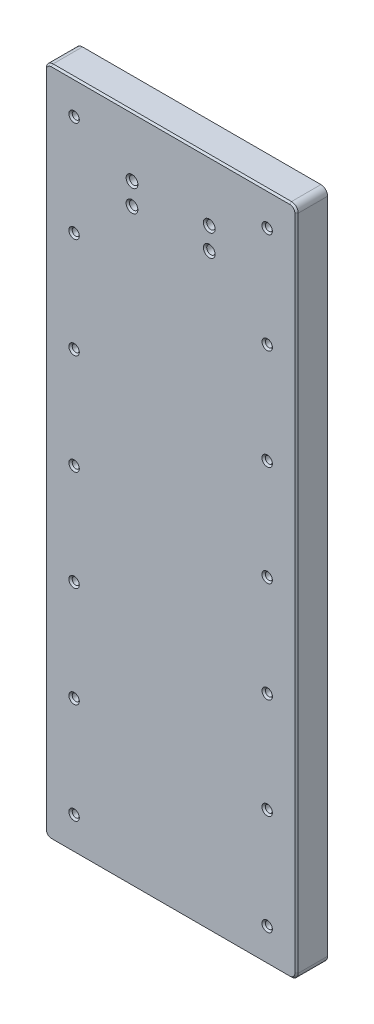
SolidWorks part; units mm, degrees
ref_plane "Front Plane" through (0, 0, 0) normal (0, 0, 1) x (1, 0, 0)
ref_plane "Top Plane" through (0, 0, 0) normal (0, 1, 0) x (1, 0, 0)
ref_plane "Right Plane" through (0, 0, 0) normal (1, 0, 0) x (0, 0, -1)
sketch "Sketch1" plane through (0, 0, 0) normal (0, 0, 1) x (1, 0, 0)
  line L1 (-14, 300) -> (136, 300)
  line L2 (-14, 300) -> (-14, -100)
  line L3 (-14, -100) -> (136, -100)
  line L4 (136, 300) -> (136, -100)
  dimension "D1" = 400
  dimension "D2" = 150
extrude "Boss-Extrude1" add sketch "Sketch1" along normal blind 18.5
sketch "Sketch10" plane through (0, 0, 18.5) normal (0, 0, 1) x (1, 0, 0)
  line L3 (104.1092, 305) -> (136, 300)
  line L4 (136, 300) -> (-14, 300)
  line L6 (17.8908, 305) -> (-14, 300)
  line L8 (61, 305) -> (17.8908, 305)
  line L9 (61, 305) -> (104.1092, 305)
sketch "Sketch2" plane through (0, 0, 0) normal (0, 0, 1) x (1, 0, 0)
  line L0 (61, 272) -> (28, 272)
  line L2 (28, 270) -> (28, 240)
  line L3 (28, 240) -> (94, 240)
  line L4 (94, 240) -> (94, 270)
  line L5 (94, 272) -> (61, 272)
  line L6 (28, 272) -> (28, 270)
  line L7 (94, 272) -> (94, 270)
extrude "Cut-Extrude1" cut sketch "Sketch2" along normal blind 11.5
fillet "Fillet1" radius 4 2 edges at (94, 240, 5.75) (28, 240, 5.75)
sketch "Sketch6" plane through (0, 0, 0) normal (0, 0, -1) x (-1, 0, 0)
  line L4 (-46, 240) -> (-76, 240)
  line L8 (-43, 240) -> (-46, 240)
  line L9 (-76, 240) -> (-79, 240)
  line L24 (-80, 240) -> (-80, 50)
  line L25 (-80, 50) -> (-80, 44)
  line L26 (-42, 50) -> (-42, 240)
  line L27 (-42, 50) -> (-42, 44)
  line L28 (-42, 44) -> (-42, -9)
  line L29 (-42, -25) -> (-42, -9)
  line L30 (-80, -25) -> (-42, -25)
  line L31 (-80, -9) -> (-80, -25)
  line L32 (-80, -9) -> (-80, 44)
  line L33 (-80, 240) -> (-79, 240)
  line L34 (-43, 240) -> (-42, 240)
extrude "Cut-Extrude3" cut sketch "Sketch6" against normal blind 8
sketch "Sketch7" plane through (0, 0, 11.5) normal (0, 0, -1) x (-1, 0, 0)
  circle A4 centre (-84, 264) radius 3.3
  circle A5 centre (-84, 251) radius 3.3
  circle A6 centre (-38, 251) radius 3.3
  circle A7 centre (-38, 264) radius 3.3
hole_wizard "M6x1.0 Tapped Hole1" positions "Sketch8" profile "Sketch9" tap size "M6x1.0" standard "ANSI Metric"
sketch "Sketch8" plane through (0, 0, 11.5) normal (0, 0, -1) x (-1, 0, 0)
  point P12 (-84, 264)
  point P15 (-38, 264)
  point P18 (-38, 251)
  point P21 (-84, 251)
sketch "Sketch9" plane through (84, 264, 11.5) normal (1, 0, 0) x (0, 1, 0)
  line L0 (0, 0) -> (0, 15)
  line L1 (0, 15) -> (2.5, 13.4978)
  line L2 (2.5, 13.4978) -> (2.5, 0)
  line L5 (2.5, 0) -> (0, 0)
  line L10 (0, 15) -> (-2.5, 13.4978) construction
  line L11 (0, -6.35) -> (0, 107.95) construction
  dimension "Tap Drill Dia." = 5
  dimension "Tap Drill Depth" = 15
  dimension "Drill Angle" = 118
cosmetic thread "Hole Thread7" parameters "D1"=12, "D2"=6
cosmetic thread "Hole Thread8" parameters "D1"=12, "D2"=6
cosmetic thread "Hole Thread9" parameters "D1"=12, "D2"=6
cosmetic thread "Hole Thread10" parameters "D1"=12, "D2"=6
sketch "Sketch11" plane through (0, 0, 0) normal (0, 0, -1) x (-1, 0, 0)
  line L2 (-61, 262) -> (-79, 262)
  line L3 (-61, 262) -> (-43, 262)
  line L4 (-43, 262) -> (-43, 273)
  line L5 (-47, 277) -> (-75, 277)
  line L6 (-79, 273) -> (-79, 262)
  arc A0 (-43, 273) -> (-47, 277) centre (-47, 273) ccw
  arc A1 (-75, 277) -> (-79, 273) centre (-75, 273) ccw
  dimension "D1" = 4
extrude "Cut-Extrude4" cut sketch "Sketch11" against normal up to surface (11.5 mm away) up to face at (81.5, 264, 11.5)
fillet "Fillet3" radius 4 4 edges at (28, 272, 5.75) (94, 272, 5.75) (43, 272, 5.75) (79, 272, 5.75)
sketch "Sketch12" plane through (0, 0, 0) normal (0, 0, -1) x (-1, 0, 0)
  line L0 (-3.5, -80) -> (-3.5, 280) construction
  line L1 (-118.5, -80) -> (-118.5, 280) construction
  line L2 (-3.5, -80) -> (-3.5, 280)
  line L3 (-118.5, -80) -> (-118.5, 280)
  circle A0 centre (-118.5, 280) radius 2.5
  circle A1 centre (-3.5, 280) radius 2.5
  circle A2 centre (-3.5, 220) radius 2.5
  circle A3 centre (-3.5, 160) radius 2.5
  circle A4 centre (-3.5, 100) radius 2.5
  circle A5 centre (-3.5, 40) radius 2.5
  circle A6 centre (-3.5, -20) radius 2.5
  circle A7 centre (-3.5, -80) radius 2.5
  circle A8 centre (-118.5, 220) radius 2.5
  circle A9 centre (-118.5, 160) radius 2.5
  circle A10 centre (-118.5, 100) radius 2.5
  circle A11 centre (-118.5, 40) radius 2.5
  circle A12 centre (-118.5, -20) radius 2.5
  circle A13 centre (-118.5, -80) radius 2.5
  dimension "D1" = 2
  dimension "D2" = 7
hole_wizard "M5x0.8 Tapped Hole1" positions "Sketch13" profile "Sketch14" tap size "M5x0.8" standard "ANSI Metric" end condition through all
sketch "Sketch13" plane through (0, 0, 0) normal (0, 0, -1) x (-1, 0, 0)
  point P0 (-118.5, 280)
  point P3 (-3.5, 280)
  point P6 (-118.5, 220)
  point P9 (-3.5, 220)
  point P12 (-3.5, 160)
  point P15 (-118.5, 160)
  point P18 (-118.5, 100)
  point P21 (-3.5, 100)
  point P24 (-3.5, 40)
  point P27 (-118.5, 40)
  point P30 (-3.5, -20)
  point P33 (-118.5, -20)
  point P36 (-118.5, -80)
  point P39 (-3.5, -80)
sketch "Sketch14" plane through (118.5, 280, 0) normal (1, 0, 0) x (0, 1, 0)
  line L0 (0, 0) -> (0, 18.5)
  line L1 (0, 18.5) -> (2.1, 18.5)
  line L2 (2.1, 18.5) -> (2.1, 0)
  line L5 (2.1, 0) -> (0, 0)
  line L11 (0, -6.35) -> (0, 107.95) construction
  dimension "Thru Tap Drill Dia." = 4.2
  dimension "Thru Tap Drill Depth" = 18.5
cosmetic thread "Hole Thread11" parameters "D2"=5
cosmetic thread "Hole Thread12" parameters "D2"=5
cosmetic thread "Hole Thread13" parameters "D2"=5
cosmetic thread "Hole Thread14" parameters "D2"=5
cosmetic thread "Hole Thread15" parameters "D2"=5
cosmetic thread "Hole Thread16" parameters "D2"=5
cosmetic thread "Hole Thread17" parameters "D2"=5
cosmetic thread "Hole Thread18" parameters "D2"=5
cosmetic thread "Hole Thread19" parameters "D2"=5
cosmetic thread "Hole Thread20" parameters "D2"=5
cosmetic thread "Hole Thread21" parameters "D2"=5
cosmetic thread "Hole Thread22" parameters "D2"=5
cosmetic thread "Hole Thread23" parameters "D2"=5
cosmetic thread "Hole Thread24" parameters "D2"=5
fillet "Fillet5" radius 4 4 edges at (-14, -100, 9.25) (136, -100, 9.25) (136, 300, 9.25) (-14, 300, 9.25)
chamfer "Chamfer2" distance 1 angle 45 26 edges at (-12.8284, 298.8284, 18.5) (61, 300, 18.5) (134.8284, 298.8284, 18.5) (136, 100, 18.5) (134.8284, -98.8284, 18.5) (61, -100, 18.5) (-12.8284, -98.8284, 18.5) (-14, 100, 18.5) (86.5, 251, 18.5) (40.5, 251, 18.5) (40.5, 264, 18.5) (86.5, 264, 18.5) (1.4, -80, 18.5) (116.4, -80, 18.5) (116.4, -20, 18.5) (1.4, -20, 18.5) (116.4, 40, 18.5) (1.4, 40, 18.5) (1.4, 100, 18.5) (116.4, 100, 18.5) (116.4, 160, 18.5) (1.4, 160, 18.5) (1.4, 220, 18.5) (116.4, 220, 18.5) (1.4, 280, 18.5) (116.4, 280, 18.5)
fillet "Fillet6" radius 4 4 edges at (42, 240, 4) (80, 240, 4) (42, -25, 4) (80, -25, 4)
chamfer "Chamfer3" distance 3 angle 45 22 edges at (41.8199, 272.6834, 0) (44.7639, 276.3166, 0) (35.7919, 272, 0) (61, 277, 0) (29.1716, 270.8284, 0) (77.2361, 276.3166, 0) (28, 256, 0) (80.1801, 272.6834, 0) (29.1716, 241.1716, 0) (86.2081, 272, 0) (35, 240, 0) (92.8284, 270.8284, 0) (40.8284, 238.8284, 0) (94, 256, 0) (42, 107.5, 0) (92.8284, 241.1716, 0) (43.1716, -23.8284, 0) (87, 240, 0) (61, -25, 0) (81.1716, 238.8284, 0) (78.8284, -23.8284, 0) (80, 107.5, 0)
